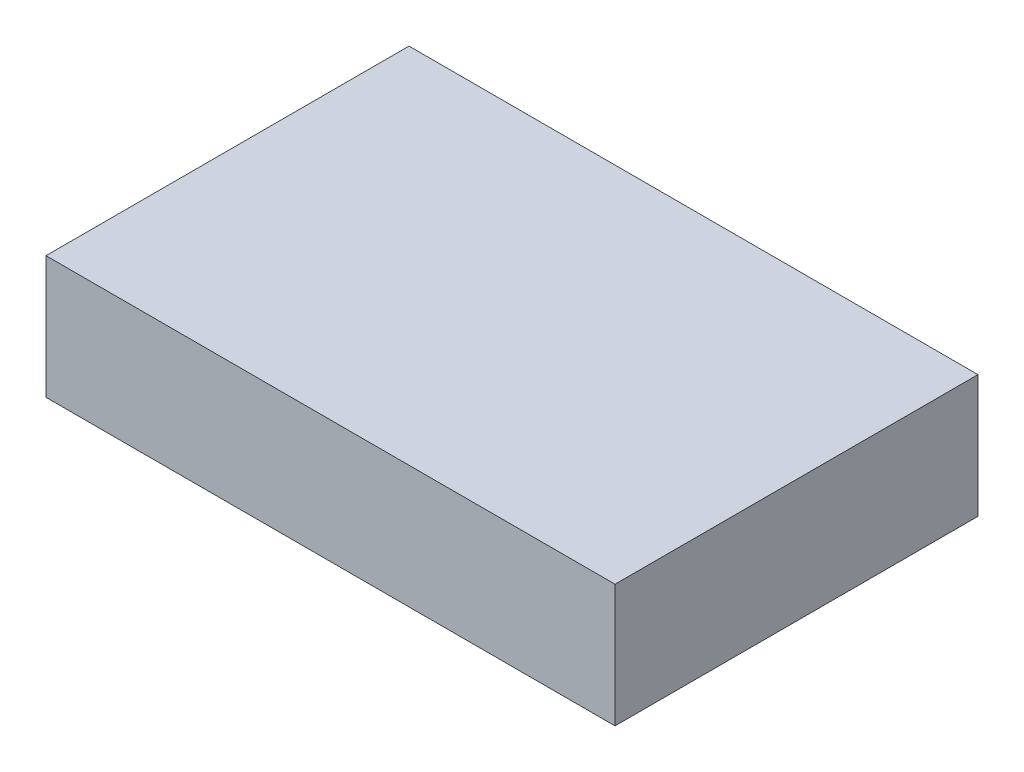
SolidWorks part; units mm, degrees
ref_plane "前基準面" through (0, 0, 0) normal (0, 0, 1) x (1, 0, 0)
ref_plane "上基準面" through (0, 0, 0) normal (0, 1, 0) x (1, 0, 0)
ref_plane "右基準面" through (0, 0, 0) normal (1, 0, 0) x (0, 0, -1)
sketch "草圖1" plane through (0, 0, 0) normal (0, 1, 0) x (1, 0, 0)
  line L1 (-44.05, 28.1) -> (44.05, 28.1)
  line L2 (-44.05, 28.1) -> (-44.05, -28.1)
  line L3 (-44.05, -28.1) -> (44.05, -28.1)
  line L4 (44.05, 28.1) -> (44.05, -28.1)
  line L5 (-44.05, 28.1) -> (44.05, -28.1) construction
  line L6 (-44.05, -28.1) -> (44.05, 28.1) construction
  point P0 (0, 0)
  dimension "D1" = 88.1
  dimension "D2" = 56.2
extrude "填料-伸長1" add sketch "草圖1" along normal blind 19
